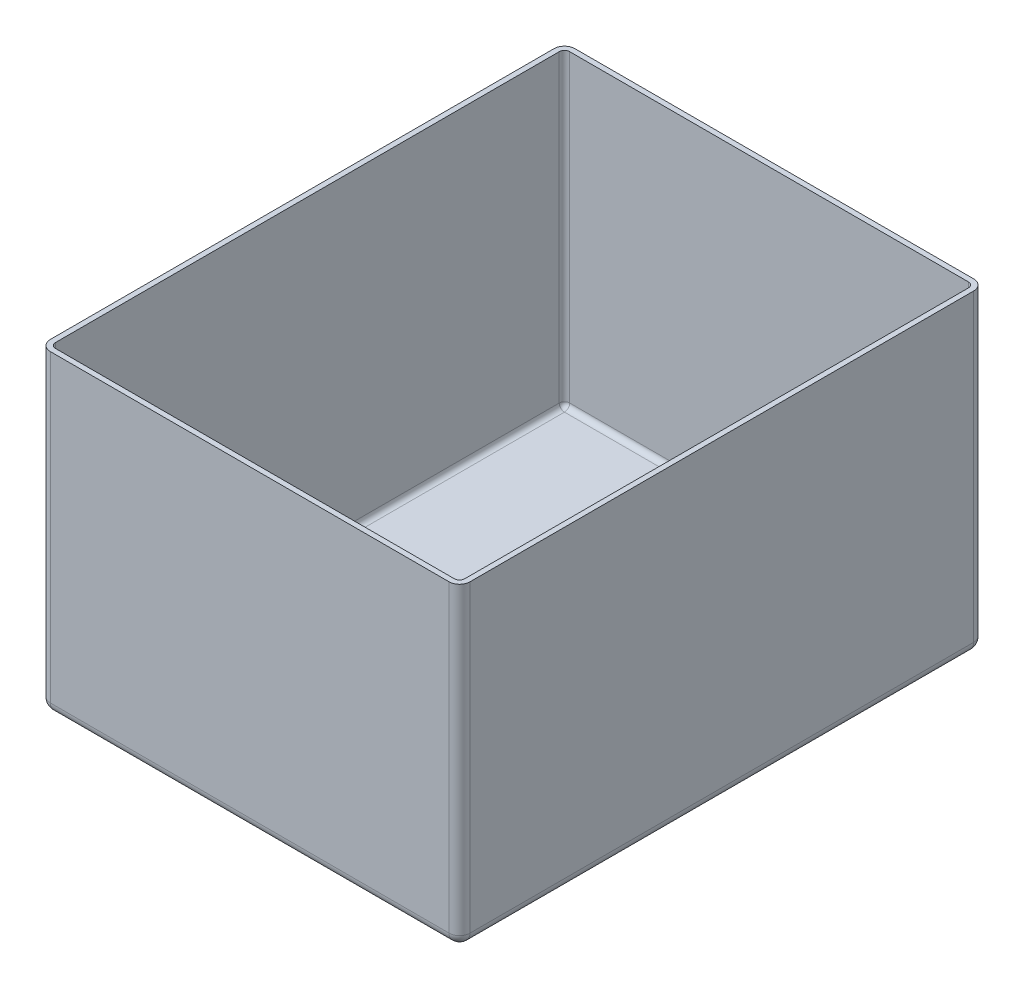
SolidWorks part; units mm, degrees
ref_plane "Alzado" through (0, 0, 0) normal (0, 0, 1) x (1, 0, 0)
ref_plane "Planta" through (0, 0, 0) normal (0, 1, 0) x (1, 0, 0)
ref_plane "Vista lateral" through (0, 0, 0) normal (1, 0, 0) x (0, 0, -1)
sketch "Croquis1" plane through (0, 0, 0) normal (0, 1, 0) x (1, 0, 0)
  line L1 (200, -250) -> (-200, -250)
  line L2 (200, -250) -> (200, 250)
  line L3 (200, 250) -> (-200, 250)
  line L4 (-200, -250) -> (-200, 250)
  line L5 (200, -250) -> (-200, 250) construction
  line L6 (200, 250) -> (-200, -250) construction
  point P0 (0, 0)
  dimension "D1" = 500
  dimension "D2" = 400
extrude "Extruir1" add sketch "Croquis1" along normal blind 300
fillet "Redondeo1" radius 10 8 edges at (0, 0, 250) (200, 0, 0) (0, 0, -250) (-200, 0, 0) (-200, 150, -250) (200, 150, -250) (200, 150, 250) (-200, 150, 250)
shell "Vaciado1" thickness 5
